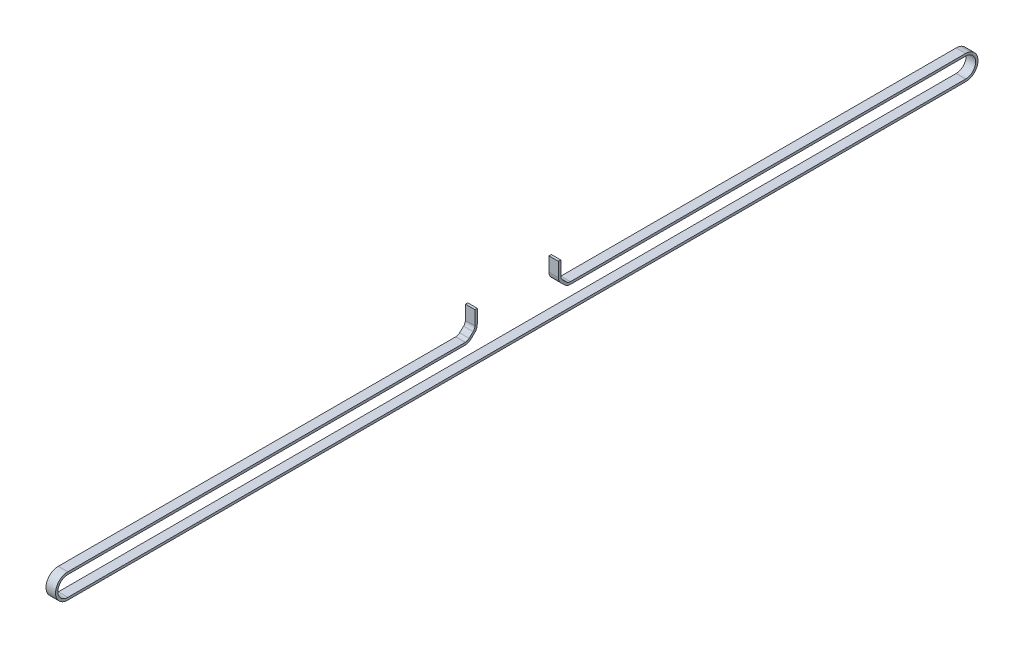
SolidWorks part; units mm, degrees
material "Rubber"
ref_plane "Plano frontal" through (0, 0, 0) normal (0, 0, 1) x (1, 0, 0)
ref_plane "Plano superior" through (0, 0, 0) normal (0, 1, 0) x (1, 0, 0)
ref_plane "Plano direito" through (0, 0, 0) normal (1, 0, 0) x (0, 0, -1)
sketch "Esboço1" plane through (0, 0, 0) normal (1, 0, 0) x (0, 0, -1)
  line L0 (-281.89, 0) -> (281.89, 0) construction
  line L1 (-281.89, 6.2) -> (281.89, 6.2)
  line L2 (-281.89, -6.2) -> (281.89, -6.2)
  line L3 (-281.89, 7.7) -> (281.89, 7.7)
  line L4 (-281.89, -7.7) -> (281.89, -7.7)
  arc A0 (-281.89, 6.2) -> (-281.89, -6.2) centre (-281.89, 0) ccw
  arc A1 (281.89, -6.2) -> (281.89, 6.2) centre (281.89, 0) ccw
  arc A2 (281.89, -7.7) -> (281.89, 7.7) centre (281.89, 0) ccw
  arc A3 (-281.89, 7.7) -> (-281.89, -7.7) centre (-281.89, 0) ccw
  point P3 (0, 0)
  dimension "D1" = 6.2
  dimension "D2" = 563.78
  dimension "D3" = 1.5
extrude "Ressalto-extrusão1" add sketch "Esboço1" along normal mid plane 6
sketch "Sketch1" plane through (0, 0, 0) normal (1, 0, 0) x (0, 0, -1)
  line L0 (26.1846, 14.4641) -> (26.1846, 11.4641) construction
  line L1 (26.1846, 14.4641) -> (26.1846, 11.4641)
  line L2 (-24.8154, 11.4641) -> (-24.8154, 14.4641) construction
  line L3 (-24.8154, 11.4641) -> (-24.8154, 14.4641)
  line L4 (-24.8154, 11.4641) -> (-30.3154, 6.2)
  line L5 (281.89, 6.2) -> (-281.89, 6.2) construction
  line L6 (-24.8154, 14.4641) -> (-26.3154, 14.4641) construction
  line L7 (-26.3154, 14.4641) -> (-26.3154, 12.1047)
  line L8 (-26.3154, 12.1047) -> (-32.4847, 6.2)
  line L9 (-32.4847, 6.2) -> (-30.3154, 6.2)
  line L10 (26.1846, 14.4641) -> (27.6846, 14.4641) construction
  line L11 (27.6846, 14.4641) -> (27.6846, 12.1047)
  line L12 (27.6846, 12.1047) -> (33.854, 6.2)
  line L13 (26.1846, 11.4641) -> (31.6846, 6.2)
  line L14 (31.6846, 6.2) -> (33.854, 6.2)
  line L15 (-26.3154, 14.4641) -> (-26.3154, 22.4641)
  line L16 (-26.3154, 22.4641) -> (-24.8154, 22.4641)
  line L17 (-24.8154, 22.4641) -> (-24.8154, 14.4641)
  line L18 (27.6846, 14.4641) -> (27.6846, 22.4641)
  line L19 (27.6846, 22.4641) -> (26.1846, 22.4641)
  line L20 (26.1846, 22.4641) -> (26.1846, 14.4641)
  dimension "D1" = 5.5
  dimension "D2" = 1.5
  dimension "D3" = 1.5
  dimension "D4" = 5.5
  dimension "D5" = 1.5
  dimension "D6" = 8
extrude "Boss-Extrude1" add sketch "Sketch1" along normal mid plane 6
sketch "Sketch2" plane through (3, 0, 0) normal (1, 0, 0) x (0, 0, -1)
  line L0 (-30.3154, 6.2) -> (-28.7481, 7.7)
  line L1 (281.89, 6.2) -> (-281.89, 6.2) construction
  line L2 (-28.7481, 7.7) -> (30.1174, 7.7)
  line L3 (30.1174, 7.7) -> (31.6846, 6.2)
  line L4 (31.6846, 6.2) -> (-30.3154, 6.2)
  line L6 (-28.7481, 7.7) -> (-24.8154, 11.4641) construction
  line L7 (26.1846, 11.4641) -> (30.1174, 7.7) construction
extrude "Cut-Extrude1" cut sketch "Sketch2" against normal through all
fillet "Fillet1" radius 5
fillet "Fillet2" radius 3.5
